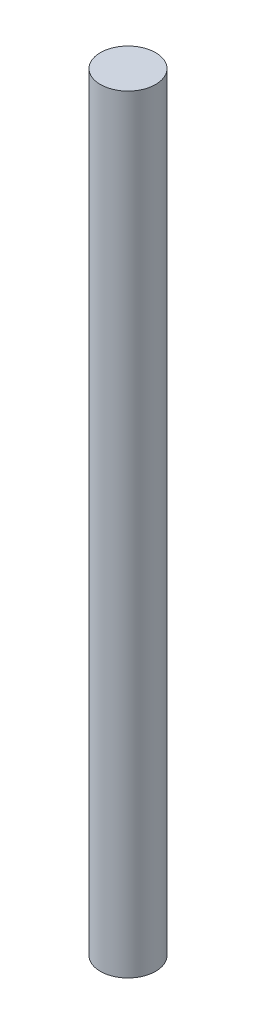
SolidWorks part; units mm, degrees
ref_plane "Plano frontal" through (0, 0, 0) normal (0, 0, 1) x (1, 0, 0)
ref_plane "Plano superior" through (0, 0, 0) normal (0, 1, 0) x (1, 0, 0)
ref_plane "Plano direito" through (0, 0, 0) normal (1, 0, 0) x (0, 0, -1)
sketch "Esboço1" plane through (0, 0, 0) normal (0, 1, 0) x (1, 0, 0)
  line L0 (0, 3.6599) -> (0, -3.8327) construction
  line L1 (4.2158, 0) -> (-4.3196, 0) construction
  circle A0 centre (0, 0) radius 2.45
  dimension "D1" = 4.9
extrude "Ressalto-extrusão3" add sketch "Esboço1" along normal blind 68.13
